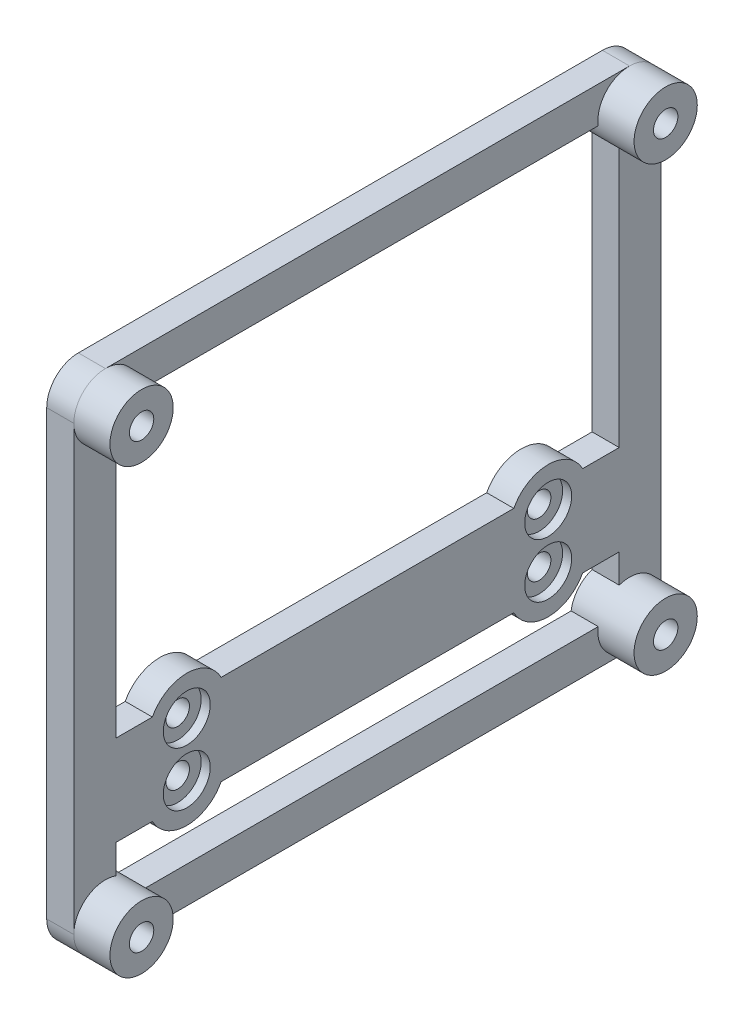
SolidWorks part; units mm, degrees
ref_plane "Front Plane" through (0, 0, 0) normal (0, 0, 1) x (1, 0, 0)
ref_plane "Top Plane" through (0, 0, 0) normal (0, 1, 0) x (1, 0, 0)
ref_plane "Right Plane" through (0, 0, 0) normal (1, 0, 0) x (0, 0, -1)
sketch "Sketch1" plane through (0, 0, 0) normal (1, 0, 0) x (0, 0, -1)
  line L1 (-32.5, -28) -> (32.5, -28)
  line L2 (-32.5, -28) -> (-32.5, 28)
  line L3 (-32.5, 28) -> (32.5, 28)
  line L4 (32.5, -28) -> (32.5, 28)
  line L5 (-32.5, -28) -> (32.5, 28) construction
  line L6 (-32.5, 28) -> (32.5, -28) construction
  line L7 (-27.8571, -24) -> (27.8571, -24)
  line L8 (-27.8571, -24) -> (-27.8571, 24)
  line L9 (-27.8571, 24) -> (27.8571, 24)
  line L10 (27.8571, -24) -> (27.8571, 24)
  line L11 (-27.8571, -24) -> (27.8571, 24) construction
  line L12 (-27.8571, 24) -> (27.8571, -24) construction
  point P0 (0, 0)
  point P6 (0, 0)
  dimension "D1" = 56
  dimension "D2" = 65
  dimension "D3" = 4
extrude "Boss-Extrude1" add sketch "Sketch1" along normal blind 3
sketch "Sketch2" plane through (3, 0, 0) normal (1, 0, 0) x (0, 0, -1)
  line L0 (32.5, 28) -> (-32.5, 28) construction
  line L1 (29, -24.5) -> (-29, -24.5)
  line L2 (29, -24.5) -> (29, 24.5)
  line L3 (29, 24.5) -> (-29, 24.5)
  line L4 (-29, -24.5) -> (-29, 24.5)
  line L5 (29, -24.5) -> (-29, 24.5) construction
  line L6 (29, 24.5) -> (-29, -24.5) construction
  line L7 (-32.5, 28) -> (-32.5, -28) construction
  line L8 (0, 0) -> (0, 28) construction
  line L9 (32.5, -28) -> (32.5, 28) construction
  line L11 (32.5, 0) -> (0, 0) construction
  circle A0 centre (-29, 24.5) radius 1.35
  circle A1 centre (-29, 24.5) radius 3.5
  circle A2 centre (29, 24.5) radius 1.35
  circle A3 centre (29, 24.5) radius 3.5
  circle A4 centre (-29, -24.5) radius 1.35
  circle A5 centre (-29, -24.5) radius 3.5
  circle A6 centre (29, -24.5) radius 1.35
  circle A7 centre (29, -24.5) radius 3.5
  point P0 (0, 0)
  point P14 (18.4795, -5.6242)
  point P15 (32.5, 0)
  line M13 (27.8571, 24) -> (27.8571, -24)
  line M14 (27.8571, -24) -> (-27.8571, -24)
  line M15 (-27.8571, -24) -> (-27.8571, 24)
  line M16 (-27.8571, 24) -> (27.8571, 24)
  dimension "D3" = 2.7
  dimension "D1" = 3.5
  dimension "D2" = 3.5
extrude "Boss-Extrude2" add sketch "Sketch2" along normal blind 4 contours L3 A1 L4 A0 | L4 A1 A0 M15 | A1 A0 M15 M16 | A1 L3 A0 M16 | A3 L3 A2 L2 | A3 A2 L3 M16 | A3 A2 M13 M16 | A3 L2 A2 M13 | A7 L2 A6 L1 | L2 A7 A6 M13 | A7 A6 M13 M14 | A7 L1 A6 M14 | A5 L1 A4 L4 | A5 L4 A4 M15 | A5 A4 M15 M14 | A5 A4 L1 M14
sketch "Sketch3" plane through (0, 0, 0) normal (-1, 0, 0) x (0, 0, 1)
  line L0 (-27.746, 24) -> (-27.8571, 24)
  line L1 (-27.8571, 24) -> (-27.8571, 23.7814)
  line L2 (27.8571, 21.1918) -> (27.8571, 23.7814)
  line L3 (27.746, 24) -> (25.5359, 24)
  line L4 (27.8571, 21.1918) -> (27.8571, 23.7814)
  line L5 (27.746, 24) -> (25.5359, 24)
  line L6 (-27.8571, 23.7814) -> (-27.8571, 21.1918)
  line L7 (-25.5359, 24) -> (-27.746, 24)
  line L8 (-27.8571, 23.7814) -> (-27.8571, 21.1918)
  line L9 (-25.5359, 24) -> (-27.746, 24)
  line L10 (-27.8571, -21.1918) -> (-27.8571, -23.7814)
  line L11 (-27.746, -24) -> (-25.5359, -24)
  line L12 (-27.8571, -21.1918) -> (-27.8571, -23.7814)
  line L13 (-27.746, -24) -> (-25.5359, -24)
  line L14 (27.8571, -23.7814) -> (27.8571, -21.1918)
  line L15 (25.5359, -24) -> (27.746, -24)
  line L16 (27.8571, -23.7814) -> (27.8571, -21.1918)
  line L17 (25.5359, -24) -> (27.746, -24)
  line L18 (27.746, 24) -> (27.8571, 24)
  line L19 (27.8571, 24) -> (27.8571, 23.7814)
  line L20 (27.746, -24) -> (27.8571, -24)
  line L21 (27.8571, -24) -> (27.8571, -23.7814)
  line L22 (-27.8571, -23.7814) -> (-27.8571, -24)
  line L23 (-27.8571, -24) -> (-27.746, -24)
  arc A2 (27.746, 24) -> (27.8571, 23.7814) centre (29, 24.5) ccw
  arc A3 (25.5359, 24) -> (27.8571, 21.1918) centre (29, 24.5) ccw
  arc A4 (27.746, 24) -> (27.8571, 23.7814) centre (29, 24.5) ccw construction
  arc A5 (25.5359, 24) -> (27.8571, 21.1918) centre (29, 24.5) ccw
  arc A6 (-27.8571, 21.1918) -> (-25.5359, 24) centre (-29, 24.5) ccw
  arc A7 (-27.8571, 23.7814) -> (-27.746, 24) centre (-29, 24.5) ccw
  arc A8 (-27.8571, 21.1918) -> (-25.5359, 24) centre (-29, 24.5) ccw
  arc A9 (-27.8571, 23.7814) -> (-27.746, 24) centre (-29, 24.5) ccw construction
  arc A10 (-27.746, -24) -> (-27.8571, -23.7814) centre (-29, -24.5) ccw
  arc A11 (-25.5359, -24) -> (-27.8571, -21.1918) centre (-29, -24.5) ccw
  arc A12 (-27.746, -24) -> (-27.8571, -23.7814) centre (-29, -24.5) ccw construction
  arc A13 (-25.5359, -24) -> (-27.8571, -21.1918) centre (-29, -24.5) ccw
  arc A14 (27.8571, -21.1918) -> (25.5359, -24) centre (29, -24.5) ccw
  arc A15 (27.8571, -23.7814) -> (27.746, -24) centre (29, -24.5) ccw
  arc A16 (27.8571, -21.1918) -> (25.5359, -24) centre (29, -24.5) ccw
  arc A17 (27.8571, -23.7814) -> (27.746, -24) centre (29, -24.5) ccw construction
  dimension "D1" = 0
  dimension "D2" = 0
  dimension "D3" = 0
  dimension "D4" = 0
extrude "Boss-Extrude3" add sketch "Sketch3" against normal up to surface (3 mm away) up to face at (3, 23.1612, 27.1493)
sketch "Sketch4" plane through (3, 0, 0) normal (1, 0, 0) x (0, 0, -1)
  circle A0 centre (29, -24.5) radius 1.35 construction
  circle A1 centre (-29, -24.5) radius 1.35 construction
  circle A2 centre (29, 24.5) radius 1.35 construction
  circle A3 centre (-29, 24.5) radius 1.35 construction
  circle A4 centre (29, -24.5) radius 1.35
  circle A5 centre (-29, -24.5) radius 1.35
  circle A6 centre (29, 24.5) radius 1.35
  circle A7 centre (-29, 24.5) radius 1.35
extrude "Cut-Extrude1" cut sketch "Sketch4" against normal through all
fillet "Fillet1" radius 3.5 4 edges at (1.5, -28, 32.5) (1.5, 28, 32.5) (1.5, -28, -32.5) (1.5, 28, -32.5)
sketch "Sketch5" plane through (3, 0, 0) normal (1, 0, 0) x (0, 0, -1)
  line L0 (27.8571, -21.1918) -> (27.8571, 21.1918) construction
  line L1 (-27.8571, -18) -> (27.8571, -18)
  line L2 (-27.8571, -18) -> (-27.8571, -8)
  line L3 (-27.8571, -8) -> (27.8571, -8)
  line L4 (27.8571, -18) -> (27.8571, -8)
  line L5 (-27.8571, -18) -> (27.8571, -8) construction
  line L6 (-27.8571, -8) -> (27.8571, -18) construction
  line L7 (-25.5359, -24) -> (25.5359, -24) construction
  line L8 (-27.8571, 21.1918) -> (-27.8571, -21.1918) construction
  point P8 (0, 0)
  point P9 (0, -2.7395)
  point P10 (0, 0)
  dimension "D1" = 10
  dimension "D2" = 6
extrude "Boss-Extrude4" add sketch "Sketch5" against normal up to surface (3 mm away) up to face at (0, -24.5, 27.65)
sketch "Sketch6" plane through (3, 0, 0) normal (1, 0, 0) x (0, 0, -1)
  line L0 (-32.5, -10) -> (32.5, -10) construction
  line L1 (-32.5, 24.5) -> (-32.5, -24.5) construction
  line L2 (32.5, -24.5) -> (32.5, 24.5) construction
  line L3 (-32.5, -16) -> (32.5, -16) construction
  line L4 (27.8571, -8) -> (-27.8571, -8) construction
  line L5 (-27.8571, -18) -> (27.8571, -18) construction
  line L6 (-20, -16) -> (0, 0) construction
  line L7 (0, 0) -> (20, -16) construction
  circle A0 centre (-20, -10) radius 1.3
  circle A1 centre (-20, -16) radius 1.3
  circle A2 centre (20, -10) radius 1.3
  circle A3 centre (20, -16) radius 1.3
  dimension "D3" = 2.6
  dimension "D1" = 2
  dimension "D2" = 2
  dimension "D4" = 40
extrude "Cut-Extrude2" cut sketch "Sketch6" against normal through all
sketch "Sketch7" plane through (3, 0, 0) normal (1, 0, 0) x (0, 0, -1)
  line L0 (27.8571, -8) -> (-27.8571, -8) construction
  line L1 (27.8571, -8) -> (-27.8571, -8)
  line L2 (-27.8571, -18) -> (27.8571, -18) construction
  line L3 (-27.8571, -18) -> (27.8571, -18)
  circle A2 centre (-20, -10) radius 4.3
  circle A3 centre (-20, -10) radius 4.3
  circle A26 centre (-20, -16) radius 4.3
  circle A27 centre (-20, -16) radius 4.3
  circle A29 centre (20, -10) radius 4.3
  circle A30 centre (20, -10) radius 4.3
  circle A32 centre (20, -16) radius 4.3
  circle A33 centre (20, -16) radius 4.3
  dimension "D1" = 3
  dimension "D2" = 3
  dimension "D3" = 3
  dimension "D4" = 3
extrude "Boss-Extrude5" add sketch "Sketch7" against normal up to surface (3 mm away) contours L1 A3 | L1 A30 | L3 A27 | L3 A33 up to face at (0, -16, 18.7)
sketch "Sketch8" plane through (3, 0, 0) normal (1, 0, 0) x (0, 0, -1)
  circle A0 centre (-20, -10) radius 2.6
  circle A1 centre (-20, -16) radius 2.6
  circle A2 centre (20, -10) radius 2.6
  circle A3 centre (20, -16) radius 2.6
  dimension "D1" = 5.2
extrude "Cut-Extrude3" cut sketch "Sketch8" against normal blind 1
